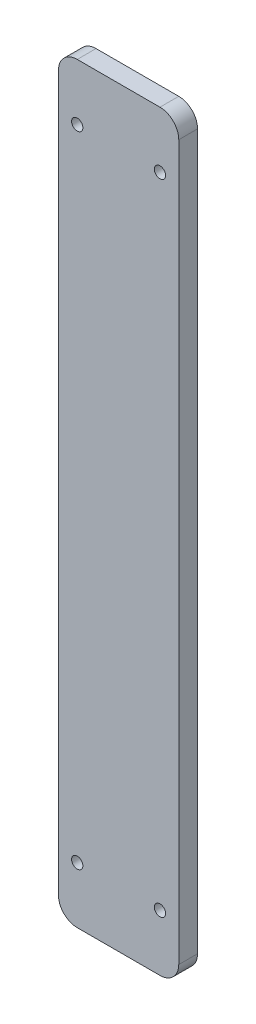
SolidWorks part; units mm, degrees
ref_plane "Plan de face" through (0, 0, 0) normal (0, 0, 1) x (1, 0, 0)
ref_plane "Plan de dessus" through (0, 0, 0) normal (0, 1, 0) x (1, 0, 0)
ref_plane "Plan de droite" through (0, 0, 0) normal (1, 0, 0) x (0, 0, -1)
sketch "Esquisse1" plane through (0, 0, 0) normal (0, 0, 1) x (1, 0, 0)
  line L1 (-16, 100) -> (16, 100)
  line L2 (-16, 100) -> (-16, -100)
  line L3 (-16, -100) -> (16, -100)
  line L4 (16, 100) -> (16, -100)
  line L5 (-16, 100) -> (16, -100) construction
  line L6 (-16, -100) -> (16, 100) construction
  point P0 (0, 0)
  dimension "D1" = 32
  dimension "D2" = 200
extrude "Boss.-Extru.1" add sketch "Esquisse1" along normal blind 5
fillet "Congé1" radius 5 4 edges at (-16, -100, 2.5) (16, -100, 2.5) (-16, 100, 2.5) (16, 100, 2.5)
sketch "Esquisse2" plane through (0, 0, 5) normal (0, 0, 1) x (1, 0, 0)
  line L0 (0, 100) -> (0, -100) construction
  line L1 (11, 100) -> (-11, 100) construction
  line L2 (-11, -100) -> (11, -100) construction
  line L3 (-16, 0) -> (16, 0) construction
  line L4 (-16, 95) -> (-16, -95) construction
  line L5 (16, -95) -> (16, 95) construction
  line L6 (-11, -100) -> (-11, 100) construction
  circle A0 centre (-11, -85) radius 1.5
  circle A1 centre (11, -85) radius 1.5
  circle A2 centre (11, 85) radius 1.5
  circle A3 centre (-11, 85) radius 1.5
  dimension "D1" = 3
  dimension "D2" = 15
extrude "Enlèv. mat.-Extru.1" cut sketch "Esquisse2" against normal blind 10
